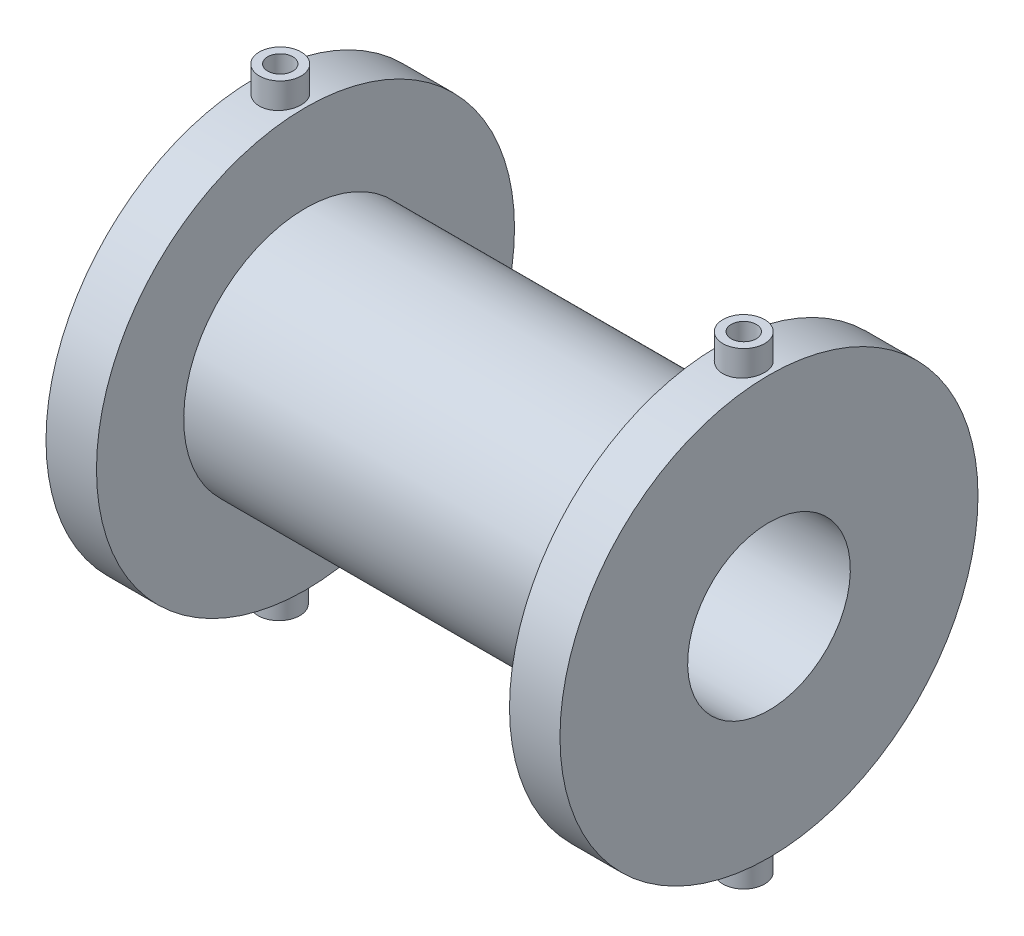
SolidWorks part; units mm, degrees
ref_plane "Alzado" through (0, 0, 0) normal (0, 0, 1) x (1, 0, 0)
ref_plane "Planta" through (0, 0, 0) normal (0, 1, 0) x (1, 0, 0)
ref_plane "Vista lateral" through (0, 0, 0) normal (1, 0, 0) x (0, 0, -1)
sketch "Ejes" plane through (0, 0, 0) normal (0, 0, 1) x (1, 0, 0)
  line L0 (-125, 0) -> (125, 0) construction
  line L1 (0, 0) -> (0, 19.5) construction
  point P5 (0, 0)
  dimension "D1" = 19.5
  dimension "D2" = 250
sketch "Camisa" plane through (0, 0, 0) normal (0, 0, 1) x (1, 0, 0)
  line L0 (-61.6, 19.5) -> (61.6, 19.5)
  line L1 (-61.6, 19.5) -> (-61.6, 50.1)
  line L2 (-61.6, 50.1) -> (-49.5, 50.1)
  line L3 (-49.5, 50.1) -> (-49.5, 29.1939)
  line L4 (-49.5, 29.1939) -> (49.5, 29.1939)
  line L5 (49.5, 29.1939) -> (49.5, 50.1)
  line L6 (49.5, 50.1) -> (61.6, 50.1)
  line L7 (61.6, 50.1) -> (61.6, 19.5)
  line L8 (51.5, 48.1) -> (59.6, 48.1)
  line L9 (59.6, 48.1) -> (59.6, 21.5)
  line L10 (51.5, 48.1) -> (51.5, 27.1939)
  line L11 (51.5, 27.1939) -> (-51.5, 27.1939)
  line L12 (59.6, 21.5) -> (-59.6, 21.5)
  line L13 (-59.6, 21.5) -> (-59.6, 48.1)
  line L14 (-59.6, 48.1) -> (-51.5, 48.1)
  line L15 (-51.5, 48.1) -> (-51.5, 27.1939)
  line L16 (0, 19.5) -> (0, 0) construction
  line L17 (125, 0) -> (-125, 0) construction
  line L18 (-55.8699, 49.8161) -> (-55.55, 50.1) construction
  line L19 (-55.8699, -50.3839) -> (-55.8699, 49.8161) construction
  line L20 (55.55, 50.1) -> (55.55, -50.1) construction
  point P2 (0, 19.5)
  point P5 (0, 19.5)
  point P16 (-49.5, 39.6469)
  point P27 (-55.55, 50.1)
  dimension "D2" = 30.6
  dimension "D3" = 12.1
  dimension "D4" = 12.1
  dimension "D5" = 9.6939
  dimension "D6" = 2
  dimension "D7" = 2
  dimension "D8" = 2
  dimension "D9" = 2
  dimension "D10" = 2
  dimension "D11" = 2
  dimension "D12" = 2
  dimension "D13" = 2
  dimension "D14" = 30.6
  dimension "D15" = 100.2
  dimension "D16" = 100.2
  dimension "D17" = 99
revolve "Revolución3" add sketch "Camisa" angle 360 about L17
ref_plane "Plano1" through (0, 50.1, 0) normal (0, 1, 0) x (1, 0, 0)
ref_plane "Plano2" through (0, 50.1, 0) normal (0, 1, 0) x (1, 0, 0)
ref_plane "Plano3" through (0, -50.1, 0) normal (0, -1, 0) x (-1, 0, 0)
ref_plane "Plano4" through (0, -50.1, 0) normal (0, -1, 0) x (-1, 0, 0)
sketch "Croquis3" plane through (0, 50.1, 0) normal (0, 1, 0) x (1, 0, 0)
  line L0 (-61.6, 0) -> (-49.5, 0) construction
  circle A0 centre (-55.55, 0) radius 5
  dimension "D1" = 10
extrude "Saliente-Extruir1" add sketch "Croquis3" along normal mid plane 12
sketch "Croquis4" plane through (0, 56.1, 0) normal (0, 1, 0) x (1, 0, 0)
  circle A0 centre (-55.55, 0) radius 3
  dimension "D1" = 6
extrude "Cortar-Extruir1" cut sketch "Croquis4" against normal blind 12
sketch "Croquis5" plane through (0, 50.1, 0) normal (0, 1, 0) x (1, 0, 0)
  line L0 (49.5, 0) -> (61.6, 0) construction
  circle A0 centre (55.55, 0) radius 5
  point P6 (55.55, 0)
  dimension "D1" = 10
extrude "Saliente-Extruir2" add sketch "Croquis5" along normal mid plane 12
sketch "Croquis8" plane through (0, -50.1, 0) normal (0, -1, 0) x (-1, 0, 0)
  circle A0 centre (55.8699, 0) radius 5
  dimension "D1" = 10
extrude "Saliente-Extruir4" add sketch "Croquis8" along normal mid plane 12
sketch "Croquis9" plane through (0, -56.1, 0) normal (0, -1, 0) x (1, 0, 0)
  circle A0 centre (-55.8699, 0) radius 3
  dimension "D1" = 6
extrude "Cortar-Extruir4" cut sketch "Croquis9" against normal blind 12
sketch "Croquis10" plane through (0, -50.1, 0) normal (0, -1, 0) x (-1, 0, 0)
  circle A0 centre (-55.55, 0) radius 5
  dimension "D1" = 10
extrude "Saliente-Extruir5" add sketch "Croquis10" along normal mid plane 12
sketch "Croquis11" plane through (0, -56.1, 0) normal (0, -1, 0) x (1, 0, 0)
  line L0 (51.5, 0) -> (59.6, 0) construction
  circle A0 centre (55.55, 0) radius 3
  dimension "D1" = 6
extrude "Cortar-Extruir5" cut sketch "Croquis11" against normal blind 12
sketch "Croquis12" plane through (0, 56.1, 0) normal (0, 1, 0) x (1, 0, 0)
sketch "Croquis14" plane through (0, 56.1, 0) normal (0, 1, 0) x (1, 0, 0)
  circle A0 centre (55.55, 0) radius 3
  circle A1 centre (55.55, 0) radius 5 construction
  dimension "D1" = 0
  dimension "D2" = 6
extrude "Cortar-Extruir7" cut sketch "Croquis14" against normal blind 16 contours A0
